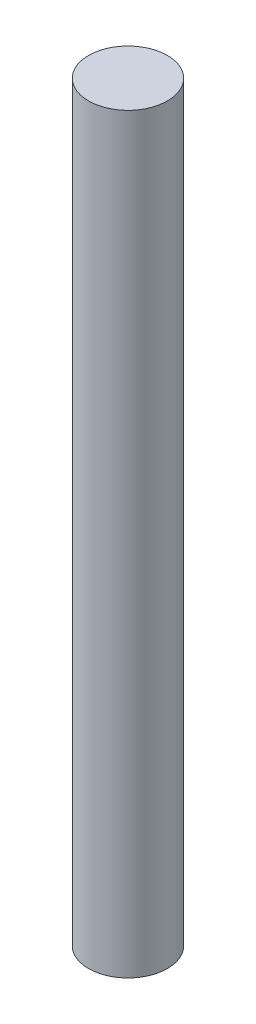
SolidWorks part; units mm, degrees
ref_plane "Ön Düzlem" through (0, 0, 0) normal (0, 0, 1) x (1, 0, 0)
ref_plane "Üst Düzlem" through (0, 0, 0) normal (0, 1, 0) x (1, 0, 0)
ref_plane "Sağ Düzlem" through (0, 0, 0) normal (1, 0, 0) x (0, 0, -1)
sketch "Çizim1" plane through (0, 0, 0) normal (0, 1, 0) x (1, 0, 0)
  circle A0 centre (0, 0) radius 7.5
  dimension "D1" = 15
extrude "Yükseklik-Ekstrüzyon1" add sketch "Çizim1" along normal blind 143
